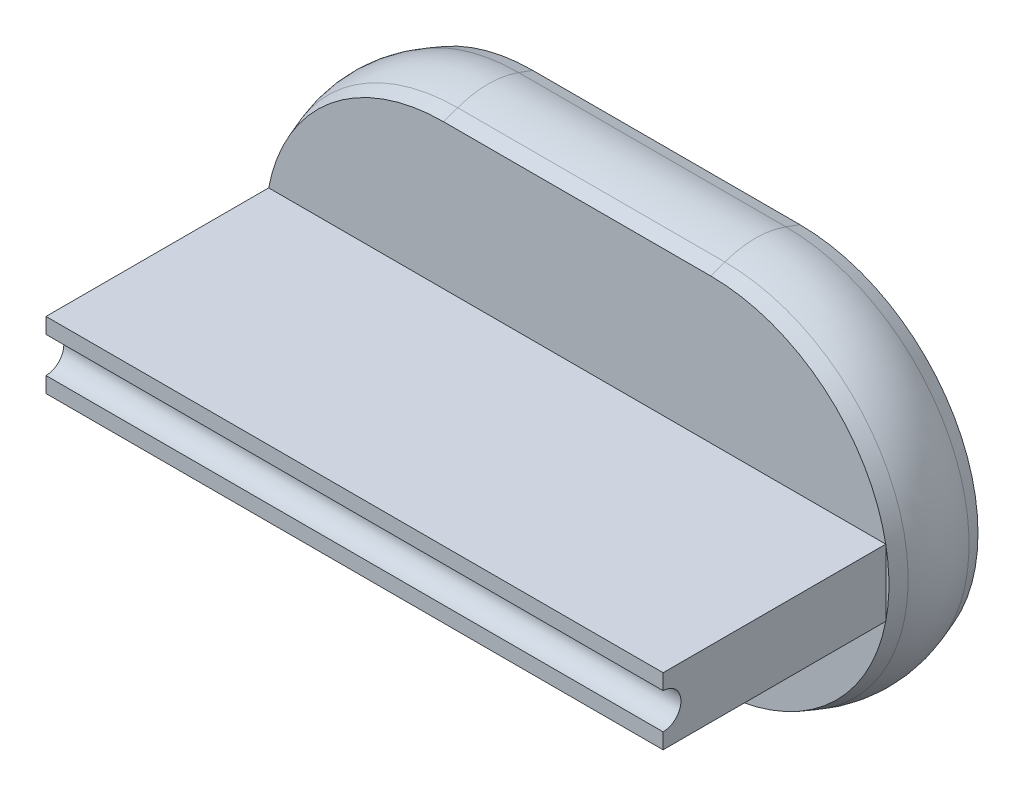
SolidWorks part; units mm, degrees
ref_plane "Front Plane" through (0, 0, 0) normal (0, 0, 1) x (1, 0, 0)
ref_plane "Top Plane" through (0, 0, 0) normal (0, 1, 0) x (1, 0, 0)
ref_plane "Right Plane" through (0, 0, 0) normal (1, 0, 0) x (0, 0, -1)
sketch "Sketch1" plane through (0, 0, 0) normal (0, 0, 1) x (1, 0, 0)
  line L0 (-20.7934, 0) -> (9.2066, 0) construction
  line L1 (-20.7934, 20) -> (9.2066, 20)
  line L2 (-20.7934, -20) -> (9.2066, -20)
  arc A0 (-20.7934, 20) -> (-20.7934, -20) centre (-20.7934, 0) ccw
  arc A1 (9.2066, -20) -> (9.2066, 20) centre (9.2066, 0) ccw
  point P3 (-5.7934, 0)
  point P8 (29.2066, 0)
  point P9 (-40.7934, 0)
  dimension "D1" = 70
  dimension "D2" = 40
extrude "Boss-Extrude1" add sketch "Sketch1" against normal blind 5 draft 20 draft outward yes
mirror "Mirror1" about plane through (-20.7934, 0, -5) normal (0, 0, 1) of "Boss-Extrude1"
fillet "Fillet1" radius 10 4 edges at (31.0265, 0, -5) (-5.7934, -21.8199, -5) (-42.6132, 0, -5) (-5.7934, 21.8199, -5)
sketch "Sketch2" plane through (0, 0, -10) normal (0, 0, -1) x (-1, 0, 0)
  line L0 (-17.4292, 0) -> (-2.8959, 0) construction
  line L1 (-17.4292, 6.7284) -> (-2.8959, 6.7284)
  line L2 (-17.4292, -6.7284) -> (-2.8959, -6.7284)
  arc A0 (-17.4292, 6.7284) -> (-17.4292, -6.7284) centre (-17.4292, 0) ccw
  arc A1 (-2.8959, -6.7284) -> (-2.8959, 6.7284) centre (-2.8959, 0) ccw
  point P3 (-10.1625, 0)
extrude "Cut-Extrude1" cut sketch "Sketch2" against normal blind 0.5
sketch "Sketch3" plane through (0, 0, -9.5) normal (0, 0, -1) x (-1, 0, 0)
  circle A0 centre (-17.45, 0) radius 3.6285
extrude "Cut-Extrude2" cut sketch "Sketch3" against normal blind 1 draft 20
sketch "Sketch4" plane through (0, 0, 0) normal (0, 0, 1) x (1, 0, 0)
  line L0 (0, 0) -> (11.789, 0) construction
  line L1 (-40.4386, -3.75) -> (28.8519, -3.75)
  line L2 (-40.4386, -3.75) -> (-40.4386, 3.75)
  line L3 (-40.4386, 3.75) -> (28.8519, 3.75)
  line L4 (28.8519, -3.75) -> (28.8519, 3.75)
  arc A0 (-20.7934, 20) -> (-20.7934, -20) centre (-20.7934, 0) ccw construction
  arc A1 (9.2066, -20) -> (9.2066, 20) centre (9.2066, 0) ccw construction
  dimension "D1" = 7.5
extrude "Boss-Extrude2" add sketch "Sketch4" along normal blind 25
sketch "Sketch5" plane through (-40.4386, 0, 0) normal (-1, 0, 0) x (0, 0, 1)
  line L0 (25, 3.75) -> (25, -3.75) construction
  arc A0 (25, 2) -> (25, -2) centre (25, 0) ccw
  dimension "D1" = 2
extrude "Cut-Extrude3" cut sketch "Sketch5" against normal blind 70 and the other way through all
